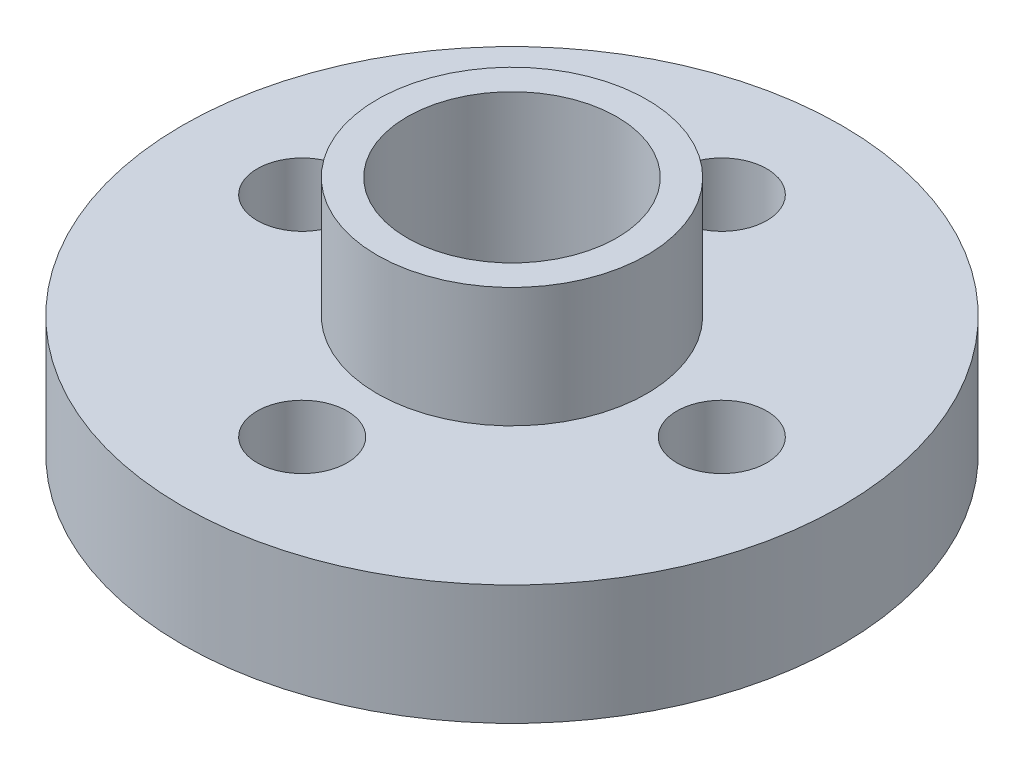
SolidWorks part; units mm, degrees
ref_plane "Front Plane" through (0, 0, 0) normal (0, 0, 1) x (1, 0, 0)
ref_plane "Top Plane" through (0, 0, 0) normal (0, 1, 0) x (1, 0, 0)
ref_plane "Right Plane" through (0, 0, 0) normal (1, 0, 0) x (0, 0, -1)
sketch "Sketch1" plane through (0, 0, 0) normal (0, 1, 0) x (1, 0, 0)
  circle A0 centre (0, 0) radius 11
  dimension "10" = 22
extrude "Boss-Extrude2" add sketch "Sketch1" along normal blind 8
sketch "Sketch3" plane through (0, 8, 0) normal (0, 1, 0) x (1, 0, 0)
  line L0 (-3, 0) -> (-11, 0) construction
  line L1 (0, 3) -> (0, 11) construction
  line L2 (0, -3) -> (0, -11) construction
  line L3 (3, 0) -> (11, 0) construction
  circle A0 centre (0, 0) radius 3
  circle A1 centre (0, 0) radius 11 construction
  circle A2 centre (-7, 0) radius 1.5
  circle A3 centre (0, 7) radius 1.5
  circle A4 centre (7, 0) radius 1.5
  circle A5 centre (0, -7) radius 1.5
  dimension "D1" = 6
  dimension "D2" = 3
  dimension "D3" = 3
  dimension "D4" = 3
  dimension "D5" = 3
extrude "Cut-Extrude2" cut sketch "Sketch3" against normal blind 12
sketch "Sketch4" plane through (0, 8, 0) normal (0, 1, 0) x (1, 0, 0)
  circle A0 centre (0, 0) radius 4.5
  circle A1 centre (0, 0) radius 11
  dimension "D1" = 9
extrude "Cut-Extrude3" cut sketch "Sketch4" against normal blind 4
sketch "Sketch6" plane through (0, 8, 0) normal (0, 1, 0) x (1, 0, 0)
  circle A0 centre (0, 0) radius 3.5
  dimension "D1" = 7
extrude "Cut-Extrude4" cut sketch "Sketch6" against normal blind 10
